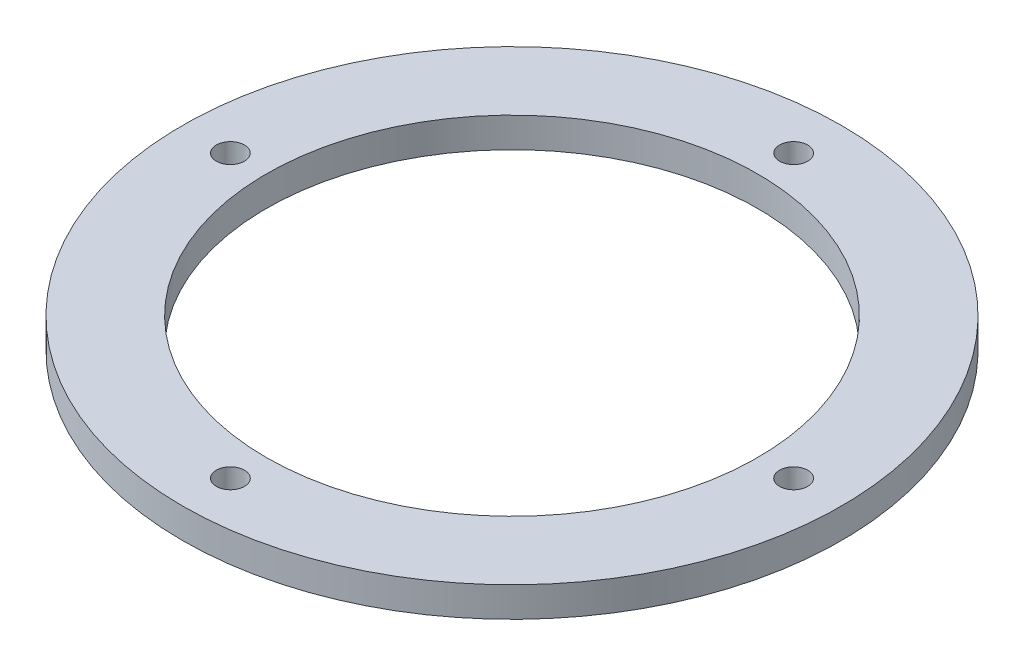
SolidWorks part; units mm, degrees
ref_plane "前视基准面" through (0, 0, 0) normal (0, 0, 1) x (1, 0, 0)
ref_plane "上视基准面" through (0, 0, 0) normal (0, 1, 0) x (1, 0, 0)
ref_plane "右视基准面" through (0, 0, 0) normal (1, 0, 0) x (0, 0, -1)
sketch "草图1" plane through (0, 0, 0) normal (0, 1, 0) x (1, 0, 0)
  line L0 (0, 0) -> (35, 0)
  line L1 (0, 0) -> (0, -35)
  circle A0 centre (0, 0) radius 40
  circle A1 centre (0, 0) radius 35
  circle A2 centre (0, 0) radius 34
  circle A3 centre (0, -34) radius 1
  circle A4 centre (0, -33) radius 2
  circle A5 centre (0, 0) radius 41
  circle A6 centre (0, 0) radius 50
  dimension "D1" = 80
  dimension "D2" = 82
  dimension "D3" = 100
sketch "草图2" plane through (0, 0, 0) normal (0, 1, 0) x (1, 0, 0)
  circle A1 centre (0, 0) radius 41 construction
  circle A3 centre (0, 0) radius 41
  circle A4 centre (0, 0) radius 55
  dimension "D2" = 110
extrude "凸台-拉伸1" add sketch "草图2" along normal blind 5
sketch "草图3" plane through (0, 0, 0) normal (0, 1, 0) x (1, 0, 0)
  line L0 (0, 0) -> (47, 0)
  circle A0 centre (0, 0) radius 45
  circle A1 centre (0, 0) radius 47
  circle A2 centre (47, 0) radius 2
sketch "草图4" plane through (0, 0, 0) normal (0, 1, 0) x (1, 0, 0)
  circle A0 centre (47, 0) radius 2 construction
  circle A1 centre (47, 0) radius 2
  circle A2 centre (0, -47) radius 2
  circle A3 centre (-47, 0) radius 2
  circle A4 centre (0, 47) radius 2
  point P12 (0, 0)
  dimension "D1" = 4
sketch "草图5" plane through (0, 0, 0) normal (0, 1, 0) x (1, 0, 0)
  circle A0 centre (0, -47) radius 2.35
  circle A3 centre (-47, 0) radius 2.35
  circle A4 centre (0, 47) radius 2.35
  circle A5 centre (47, 0) radius 2.35
  dimension "D1" = 4.7
  dimension "D2" = 4.7
  dimension "D3" = 4.7
  dimension "D4" = 4.7
extrude "切除-拉伸2" cut sketch "草图5" along normal up to surface (5 mm away) up to face at (0, 5, 55)
fillet "圆角1" radius 1 4 edges at (0, 0, -44.65) (47, 0, 2.35) (0, 0, 49.35) (-47, 0, 2.35)
